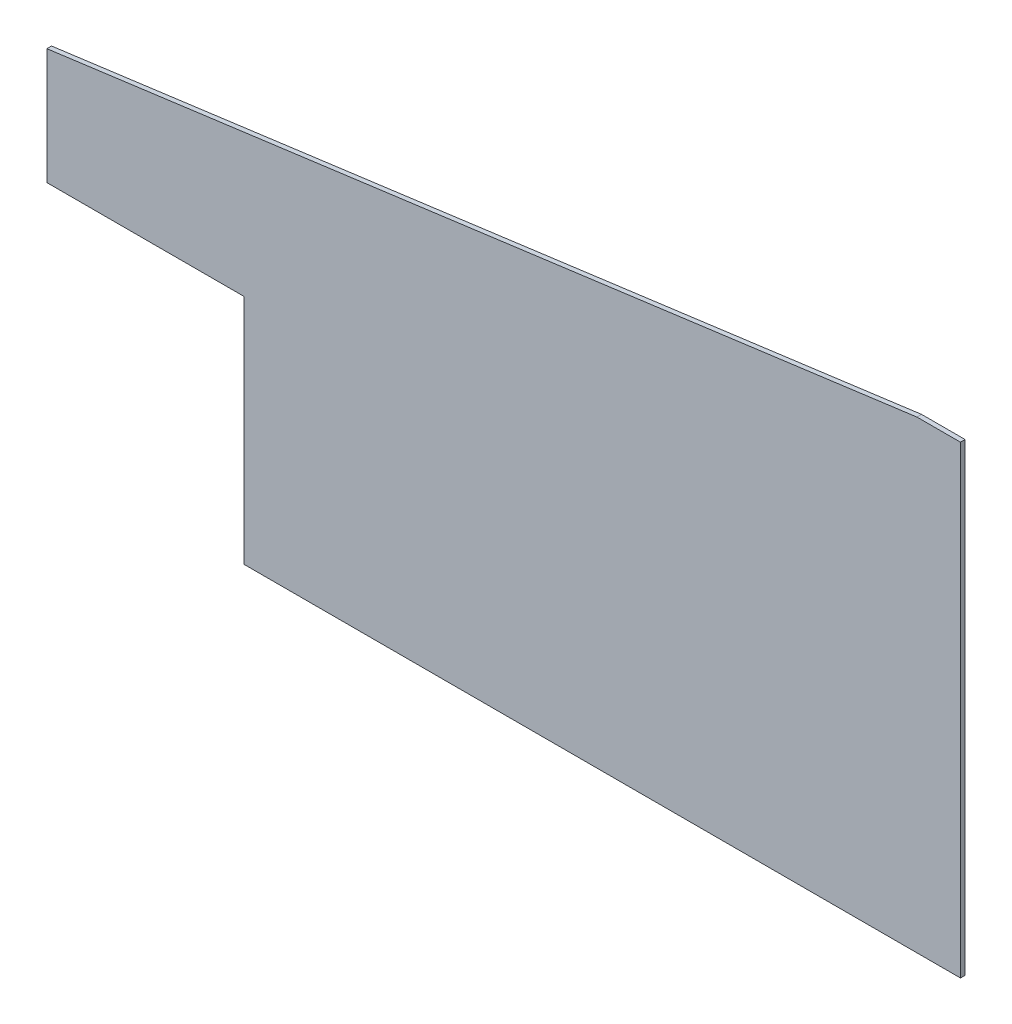
SolidWorks part; units mm, degrees
material "ABS"
ref_plane "Front Plane" through (0, 0, 0) normal (0, 0, 1) x (1, 0, 0)
ref_plane "Top Plane" through (0, 0, 0) normal (0, 1, 0) x (1, 0, 0)
ref_plane "Right Plane" through (0, 0, 0) normal (1, 0, 0) x (0, 0, -1)
sketch "Sketch1" plane through (0, 0, 0) normal (0, 0, 1) x (1, 0, 0)
  line L1 (-787.5, -100) -> (-787.5, -200)
  line L2 (-787.5, -200) -> (-617.5, -200)
  line L3 (-617.5, -200) -> (-617.5, -400)
  line L4 (-617.5, -400) -> (0, -400)
  line L5 (0, -400) -> (0, 0)
  line L6 (0, 0) -> (-37.5, 0)
  line L7 (-787.5, -100) -> (-37.5, 0)
  dimension "D1" = 37.5
  dimension "D2" = 170
  dimension "D3" = 787.5
  dimension "D4" = 100
  dimension "D5" = 400
  dimension "D6" = 200
extrude "Boss-Extrude1" add sketch "Sketch1" along normal blind 4
